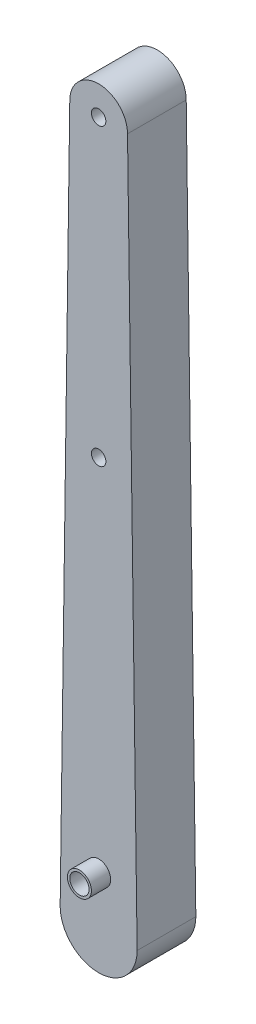
SolidWorks part; units mm, degrees
ref_plane "Front Plane" through (0, 0, 0) normal (0, 0, 1) x (1, 0, 0)
ref_plane "Top Plane" through (0, 0, 0) normal (0, 1, 0) x (1, 0, 0)
ref_plane "Right Plane" through (0, 0, 0) normal (1, 0, 0) x (0, 0, -1)
sketch "Sketch2" plane through (0, 0, 0) normal (0, 0, 1) x (1, 0, 0)
  line L0 (0, 76.3587) -> (0, -69.6413) construction
  line L1 (6, 76.3587) -> (8, -69.6413)
  line L2 (-6, 76.3587) -> (-8, -69.6413)
  arc A1 (-8, -69.6413) -> (8, -69.6413) centre (0, -69.6413) ccw
  arc A2 (6, 76.3587) -> (-6, 76.3587) centre (0, 76.3587) ccw
  circle A3 centre (0, 76.3587) radius 1.5
  point P3 (0, 0.3587)
  point P8 (0, 82.3587)
  point P9 (0, -77.6413)
  dimension "D1" = 6
  dimension "D2" = 8
  dimension "D4" = 3
  dimension "D3" = 160
extrude "Boss-Extrude1" add sketch "Sketch2" along normal blind 12.2
sketch "Sketch3" plane through (0, 0, 12.2) normal (0, 0, 1) x (1, 0, 0)
  circle A0 centre (0, -59.6413) radius 2.5
  arc A1 (-8, -69.6413) -> (8, -69.6413) centre (0, -69.6413) ccw construction
  point P5 (0, -77.6413)
  dimension "D1" = 5
  dimension "D2" = 18
extrude "Boss-Extrude2" add sketch "Sketch3" along normal blind 4 separate body
sketch "Sketch4" plane through (0, 0, 16.2) normal (0, 0, 1) x (1, 0, 0)
  circle A0 centre (0, -59.6413) radius 2
  dimension "D1" = 4
extrude "Cut-Extrude1" cut sketch "Sketch4" against normal blind 2
sketch "Sketch5" plane through (0, 0, 0) normal (0, 0, -1) x (-1, 0, 0)
  circle A0 centre (0, -59.6413) radius 2 construction
  circle A1 centre (0, -59.6413) radius 2
extrude "Cut-Extrude2" cut sketch "Sketch5" against normal blind 20
sketch "Sketch7" plane through (0, 0, 12.2) normal (0, 0, 1) x (1, 0, 0)
  circle A0 centre (0, 15.11) radius 1.5
  dimension "D1" = 3
extrude "Cut-Extrude3" cut sketch "Sketch7" against normal blind 20
